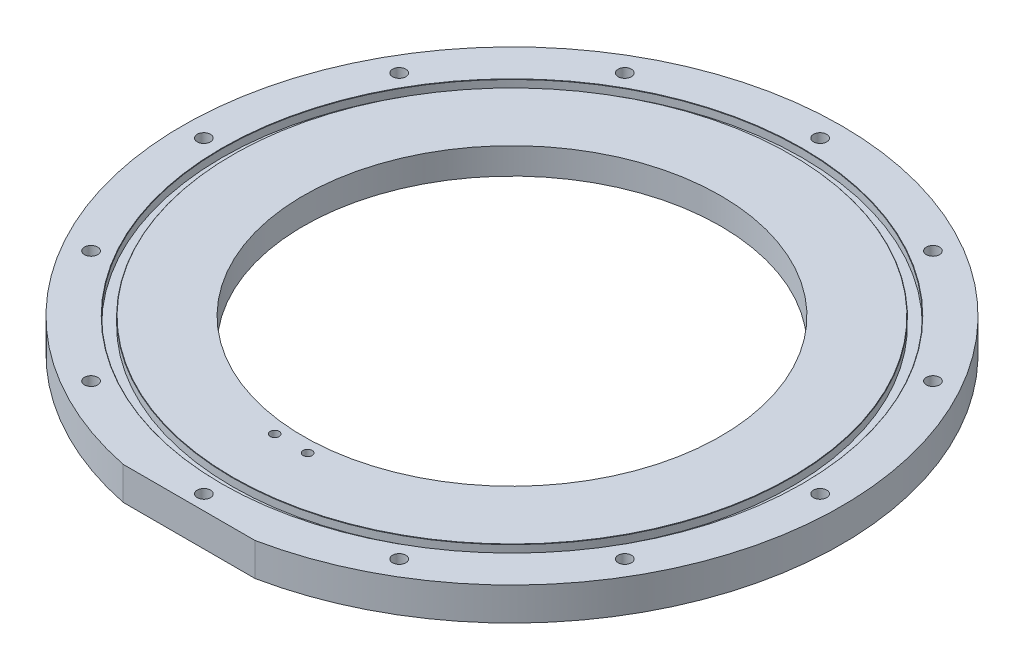
SolidWorks part; units mm, degrees
material "AISI 304"
ref_plane "Front" through (0, 0, 0) normal (0, 0, 1) x (1, 0, 0)
ref_plane "Top" through (0, 0, 0) normal (0, 1, 0) x (1, 0, 0)
ref_plane "Right" through (0, 0, 0) normal (1, 0, 0) x (0, 0, -1)
sketch "Sketch1" plane through (0, 0, 0) normal (0, 0, 1) x (1, 0, 0)
  line L0 (0, 0) -> (0, 12.7) construction
  line L1 (109.7915, 0) -> (109.7915, 2.54)
  line L2 (109.7915, 0) -> (127, 0)
  line L3 (127, 0) -> (127, 12.7)
  line L4 (127, 12.7) -> (105.7783, 12.7)
  line L5 (109.7915, 2.54) -> (105.7783, 2.54)
  line L6 (105.7783, 2.54) -> (105.7783, 12.7) construction
  line L7 (105.7783, 12.7) -> (80.3783, 12.7)
  line L8 (80.3783, 12.7) -> (80.3783, 2.54)
  line L9 (80.3783, 2.54) -> (105.7783, 2.54)
  dimension "D1" = 219.583
  dimension "D2" = 254
  dimension "D3" = 12.7
  dimension "D4" = 105.7783
  dimension "D5" = 25.4
  dimension "D6" = 2.54
revolve "Revolve1" add sketch "Sketch1" angle 360 about L0
hole_wizard "1/4-20 Tapped Hole1" positions "Sketch2" profile "Sketch3" tap size "1/4-20" standard "ANSI Inch" end condition up to next
sketch "Sketch2" plane through (0, 12.7, 0) normal (0, 1, 0) x (1, 0, 0)
  line L0 (0, 0) -> (0, 118.745) construction
  point P0 (0, 118.745)
  point P6 (59.3725, 102.8362)
  point P7 (102.8362, 59.3725)
  point P8 (118.745, 0)
  point P9 (102.8362, -59.3725)
  point P10 (59.3725, -102.8362)
  point P11 (0, -118.745)
  point P12 (-59.3725, -102.8362)
  point P13 (-102.8362, -59.3725)
  point P18 (-118.745, 0)
  point P19 (-102.8362, 59.3725)
  point P20 (-59.3725, 102.8362)
  dimension "D2" = 118.745
  dimension "D1" = 12
sketch "Sketch3" plane through (0, 12.7, -118.745) normal (1, 0, 0) x (0, 0, 1)
  line L0 (0, 0) -> (0, 12.7)
  line L1 (0, 12.7) -> (2.5527, 12.7)
  line L2 (2.5527, 12.7) -> (2.5527, 0)
  line L5 (2.5527, 0) -> (0, 0)
  line L11 (0, -6.35) -> (0, 107.95) construction
  dimension "Thru Tap Drill Dia." = 5.1054
  dimension "Thru Tap Drill Depth" = 12.7
cosmetic thread "Hole Thread1" parameters "D2"=6.35
cosmetic thread "Hole Thread2" parameters "D2"=6.35
cosmetic thread "Hole Thread3" parameters "D2"=6.35
cosmetic thread "Hole Thread4" parameters "D2"=6.35
cosmetic thread "Hole Thread5" parameters "D2"=6.35
cosmetic thread "Hole Thread6" parameters "D2"=6.35
cosmetic thread "Hole Thread7" parameters "D2"=6.35
cosmetic thread "Hole Thread8" parameters "D2"=6.35
cosmetic thread "Hole Thread9" parameters "D2"=6.35
cosmetic thread "Hole Thread12" parameters "D2"=6.35
cosmetic thread "Hole Thread13" parameters "D2"=6.35
cosmetic thread "Hole Thread14" parameters "D2"=6.35
sketch "Sketch4" plane through (0, 0, 0) normal (0, 0, 1) x (1, 0, 0)
  line L0 (0, 12.7) -> (0, 0) construction
  line L2 (127, 12.7) -> (-127, 12.7) construction
  line L3 (107.7468, 12.7) -> (111.8108, 12.7)
  line L4 (107.7468, 12.7) -> (107.7468, 9.6266)
  line L5 (107.7468, 9.6266) -> (111.8108, 9.6266)
  line L6 (111.8108, 12.7) -> (111.8108, 9.6266)
  line L7 (80.3783, 12.7) -> (-80.3783, 12.7) construction
  dimension "D1" = 215.4936
  dimension "D2" = 223.6216
  dimension "D3" = 3.0734
  dimension "D4" = 4.064
revolve "Cut-Revolve1" cut sketch "Sketch4" angle 360 about L0
chamfer "Chamfer1" distance 0.127 angle 45 2 edges at (0, 12.7, 107.7468) (0, 12.7, 111.8108)
hole_wizard "#8-32 Tapped Hole1" positions "Sketch5" profile "Sketch6" tap size "#8-32" standard "ANSI Inch" end condition up to next
sketch "Sketch5" plane through (0, 2.54, 0) normal (0, -1, 0) x (-1, 0, 0)
  line L0 (-6.35, -85.09) -> (6.35, -85.09) construction
  line L2 (0, -85.09) -> (0, 0) construction
  point P0 (6.35, -85.09)
  point P2 (-6.35, -85.09)
  dimension "D1" = 12.7
  dimension "D2" = 85.09
sketch "Sketch6" plane through (-6.35, 2.54, 85.09) normal (1, 0, 0) x (0, 0, -1)
  line L0 (0, 0) -> (0, 10.16)
  line L1 (0, 10.16) -> (1.7272, 10.16)
  line L2 (1.7272, 10.16) -> (1.7272, 0)
  line L5 (1.7272, 0) -> (0, 0)
  line L11 (0, -6.35) -> (0, 107.95) construction
  dimension "Thru Tap Drill Dia." = 3.4544
  dimension "Thru Tap Drill Depth" = 10.16
cosmetic thread "Hole Thread10" parameters "D2"=4.1656
cosmetic thread "Hole Thread11" parameters "D2"=4.1656
sketch "Sketch7" plane through (0, 12.7, 0) normal (0, 1, 0) x (1, 0, 0)
  line L1 (-25.4, -124.4341) -> (25.4, -124.4341)
  line L2 (-25.4, -124.4341) -> (-25.4, -127)
  line L3 (-25.4, -127) -> (25.4, -127)
  line L4 (25.4, -124.4341) -> (25.4, -127)
  circle A0 centre (0, 0) radius 127 construction
  dimension "D1" = 50.8
extrude "Cut-Extrude1" cut sketch "Sketch7" against normal up to next
sketch "Sketch8" plane through (0, 12.7, 0) normal (0, 1, 0) x (1, 0, 0)
  line L0 (-80.3783, 0) -> (0, 0) construction
  line L1 (0, 0) -> (35.921, 35.921) construction
  circle A0 centre (0, 0) radius 80.3783 construction
  circle A1 centre (35.921, 35.921) radius 16
  dimension "D1" = 32
  dimension "D2" = 135
  dimension "D3" = 50.8
